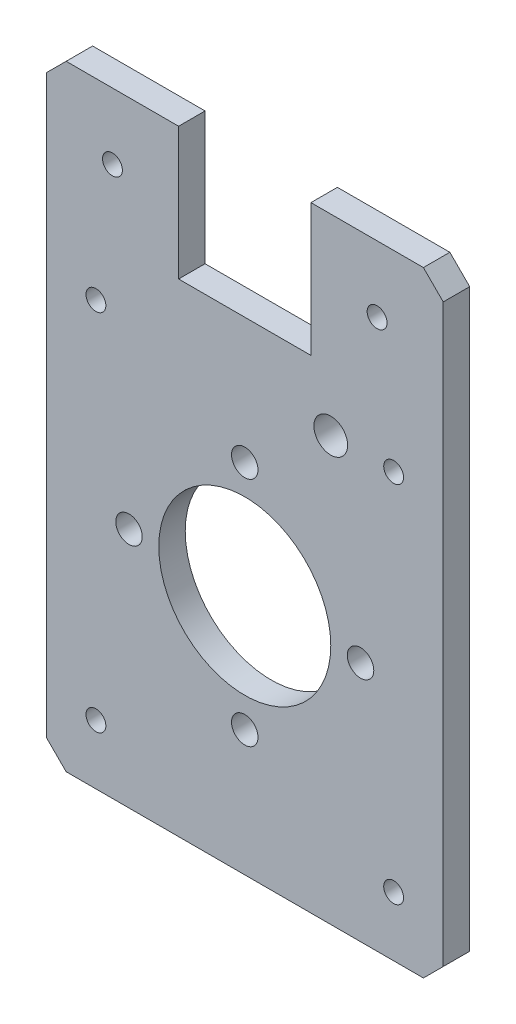
SolidWorks part; units mm, degrees
material "3003 Alloy"
ref_plane "Front Plane" through (0, 0, 0) normal (0, 0, 1) x (1, 0, 0)
ref_plane "Top Plane" through (0, 0, 0) normal (0, 1, 0) x (1, 0, 0)
ref_plane "Right Plane" through (0, 0, 0) normal (1, 0, 0) x (0, 0, -1)
sketch "Sketch1" plane through (0, 0, 0) normal (0, 0, 1) x (1, 0, 0)
  line L1 (0, 0) -> (60, 0)
  line L2 (0, 0) -> (0, 73)
  line L3 (0, 73) -> (60, 73)
  line L4 (60, 0) -> (60, 73)
extrude "Boss-Extrude1" add sketch "Sketch1" along normal blind 6
sketch "Sketch2" plane through (0, 0, 0) normal (0, 0, -1) x (-1, 0, 0)
  circle A0 centre (-30, 36.5) radius 8
extrude "Cut-Extrude1" cut sketch "Sketch2" against normal through all
sketch "Sketch3" plane through (0, 0, 0) normal (0, 0, -1) x (-1, 0, 0)
  circle A0 centre (-52.5, 64) radius 1.5
  circle A1 centre (-7.5, 64) radius 1.5
  circle A2 centre (-52.5, 9) radius 1.5
  circle A3 centre (-7.5, 9) radius 1.5
extrude "Cut-Extrude2" cut sketch "Sketch3" against normal through all
sketch "Sketch4" plane through (0, 0, 0) normal (0, 0, -1) x (-1, 0, 0)
  circle A0 centre (-30, 36.5) radius 21
extrude "Cut-Extrude3" cut sketch "Sketch4" against normal blind 4
sketch "Sketch5" plane through (0, 0, 0) normal (0, 0, -1) x (-1, 0, 0)
  line L0 (0, 73) -> (0, 93)
  line L1 (0, 93) -> (-20, 93)
  line L2 (-20, 93) -> (-20, 73)
  line L3 (-60, 73) -> (0, 73) construction
  line L4 (-20, 73) -> (-40, 73)
  line L5 (-40, 73) -> (-40, 93)
  line L6 (-40, 93) -> (-60, 93)
  line L7 (-60, 93) -> (-60, 73)
  line M7 (0, 73) -> (-60, 73)
extrude "Boss-Extrude2" add sketch "Sketch5" against normal blind 6 contours L6 L7 L5 M7 | L1 L2 L0 M7
sketch "Sketch6" plane through (0, 0, 0) normal (0, 0, -1) x (-1, 0, 0)
  circle A0 centre (-10, 83) radius 1.5
  circle A1 centre (-50, 83) radius 1.5
extrude "Cut-Extrude4" cut sketch "Sketch6" against normal blind 10
chamfer "Chamfer1" distance 3 angle 45 2 edges at (0, 0, 3) (60, 0, 3)
chamfer "Chamfer2" distance 3 angle 45 2 edges at (60, 93, 3) (0, 93, 3)
sketch "Sketch7" plane through (0, 0, 4) normal (0, 0, -1) x (-1, 0, 0)
  circle A1 centre (-30, 54) radius 2
  circle A2 centre (-12.5, 36.5) radius 2
  circle A3 centre (-30, 19) radius 2
  circle A4 centre (-47.5, 36.5) radius 2
  point P14 (-30, 36.5)
  dimension "D1" = 4
extrude "Cut-Extrude5" cut sketch "Sketch7" against normal through all
sketch "Sketch8" plane through (0, 0, 4) normal (0, 0, -1) x (-1, 0, 0)
  circle A0 centre (-30, 36.5) radius 13
extrude "Cut-Extrude6" cut sketch "Sketch8" against normal through all
sketch "Sketch9" plane through (0, 0, 4) normal (0, 0, -1) x (-1, 0, 0)
  circle A0 centre (-47.5, 36.5) radius 2 construction
  circle A1 centre (-30, 36.5) radius 21
  circle A2 centre (-30, 36.5) radius 21
  circle A3 centre (-30, 19) radius 2 construction
  circle A4 centre (-12.5, 36.5) radius 2 construction
  circle A5 centre (-30, 54) radius 2 construction
  circle A6 centre (-47.5, 36.5) radius 2
  circle A7 centre (-30, 19) radius 2
  circle A8 centre (-12.5, 36.5) radius 2
  circle A9 centre (-30, 54) radius 2
  circle M2 centre (-30, 36.5) radius 13
  circle M3 centre (-30, 54) radius 2
  circle M4 centre (-12.5, 36.5) radius 2
  circle M5 centre (-30, 19) radius 2
  circle M6 centre (-47.5, 36.5) radius 2
  circle M7 centre (-30, 36.5) radius 21
  dimension "D1" = 0
extrude "Boss-Extrude3" add sketch "Sketch9" along normal blind 4 contours M7 M3 M5 M6 M4 M2
sketch "Sketch11" plane through (0, 0, 6) normal (0, 0, 1) x (1, 0, 0)
  line L12 (60, 3) -> (60, 90)
  line L13 (60, 90) -> (57, 93)
  line L14 (57, 93) -> (40, 93)
  line L15 (40, 93) -> (40, 73)
  line L16 (40, 73) -> (20, 73)
  line L17 (20, 73) -> (20, 93)
  line L18 (20, 93) -> (3, 93)
  line L19 (3, 93) -> (0, 90)
  line L20 (0, 90) -> (0, 3)
  line L21 (0, 3) -> (3, 0)
  line L22 (3, 0) -> (57, 0)
  line L23 (57, 0) -> (60, 3)
  line L24 (60, 3) -> (60, 90)
  line L25 (60, 90) -> (57, 93)
  line L26 (57, 93) -> (40, 93)
  line L27 (40, 93) -> (40, 73)
  line L28 (40, 73) -> (20, 73)
  line L29 (20, 73) -> (20, 93)
  line L30 (20, 93) -> (3, 93)
  line L31 (3, 93) -> (0, 90)
  line L32 (0, 90) -> (0, 3)
  line L33 (0, 3) -> (3, 0)
  line L34 (3, 0) -> (57, 0)
  line L35 (57, 0) -> (60, 3)
  dimension "D1" = 0
extrude "Cut-Extrude7" cut sketch "Sketch11" against normal blind 2
sketch "Sketch12" plane through (0, 0, 4) normal (0, 0, 1) x (1, 0, 0)
  circle A2 centre (43, 64) radius 2.55
extrude "Cut-Extrude8" cut sketch "Sketch12" against normal blind 10
